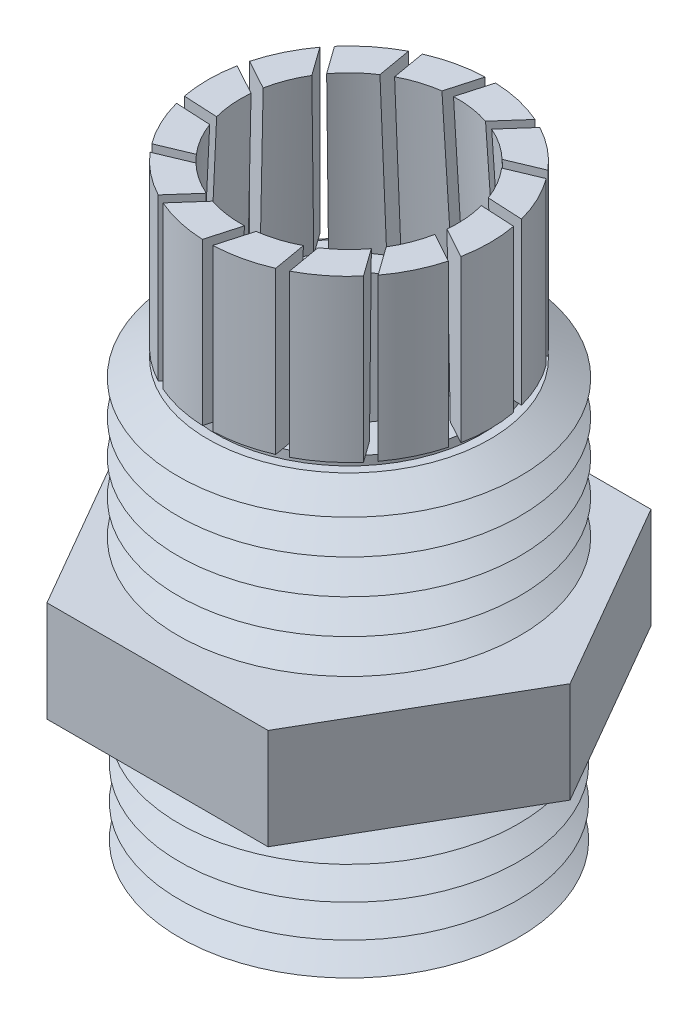
SolidWorks part; units mm, degrees
ref_plane "Front Plane" through (0, 0, 0) normal (0, 0, 1) x (1, 0, 0)
ref_plane "Top Plane" through (0, 0, 0) normal (0, 1, 0) x (1, 0, 0)
ref_plane "Right Plane" through (0, 0, 0) normal (1, 0, 0) x (0, 0, -1)
sketch "Sketch1" plane through (0, 0, 0) normal (0, 0, 1) x (1, 0, 0)
  line L0 (-5, -1.7) -> (-5, -14.9666)
  line L1 (0, -55) -> (0, 55) construction
  line L2 (-7, 7) -> (-7, 15)
  line L4 (-7, -7) -> (-7, -2)
  line L5 (-7, 15) -> (-5.3716, 15)
  line L6 (-5, -1.7) -> (-4.5951, 7)
  line L7 (-7, -14.9666) -> (-8.41, -14.1525)
  line L8 (-7, -2) -> (-8.4815, -1.1446)
  line L9 (-7, -13.3385) -> (-8.41, -14.1525)
  line L10 (-7, -14.9666) -> (-5, -14.9666)
  line L11 (-7, -13.3385) -> (-8.41, -12.5244)
  line L12 (-7, -11.7103) -> (-8.41, -12.5244)
  line L13 (-7, -0.2893) -> (-8.4815, -1.1446)
  line L14 (-7, -11.7103) -> (-8.41, -10.8963)
  line L15 (-7, -10.0822) -> (-8.41, -10.8963)
  line L16 (-7, -10.0822) -> (-8.41, -9.2681)
  line L17 (-7, -8.4541) -> (-8.41, -9.2681)
  line L18 (-7, -0.2893) -> (-8.4815, 0.5661)
  line L19 (-7, -8.4541) -> (-8.41, -7.64)
  line L20 (-7, 1.4215) -> (-8.4815, 0.5661)
  line L21 (-8.41, -7.64) -> (-7, -7)
  line L22 (-7, 6.5537) -> (-6.8008, 6.5537)
  line L23 (-6.8008, 6.5537) -> (-6.5772, 6.5537)
  line L24 (-7, 1.4215) -> (-8.4815, 2.2769)
  line L25 (-7, 3.1322) -> (-8.4815, 2.2769)
  line L26 (-7, 3.1322) -> (-8.4815, 3.9876)
  line L27 (-7, 4.843) -> (-8.4815, 3.9876)
  line L28 (-6.5772, 6.5537) -> (-6.5772, 7)
  line L29 (-7, 4.843) -> (-8.4815, 5.6983)
  line L30 (-7, 6.5537) -> (-8.4815, 5.6983)
  line L32 (-6.5772, 7) -> (-7, 7)
  line L33 (-5.3716, 7) -> (-4.5951, 7)
  line L34 (-5.3716, 15) -> (-5.7537, 7)
  line L35 (-5.7537, 7) -> (-5.3716, 7)
  dimension "D1" = 5
ref_axis "Axis1" through (0, -16.4649, 0) along (0, 1, 0)
revolve "Revolve1" add sketch "Sketch1" angle 360 about axis through (0, -16.4649, 0) along (0, 1, 0)
ref_plane "Plane1" through (0, -4.4666, 0) normal (0, -1, 0) x (1, 0, 0)
sketch "Sketch2" plane through (0, -4.4666, 0) normal (0, -1, 0) x (1, 0, 0)
  line L1 (10.9697, 0) -> (5.4848, 9.5)
  line L2 (5.4848, 9.5) -> (-5.4848, 9.5)
  line L3 (-5.4848, 9.5) -> (-10.9697, 0)
  line L4 (-10.9697, 0) -> (-5.4848, -9.5)
  line L5 (-5.4848, -9.5) -> (5.4848, -9.5)
  line L6 (5.4848, -9.5) -> (10.9697, 0)
  circle A0 centre (0, 0) radius 9.5 construction
extrude "Boss-Extrude1" add sketch "Sketch2" along normal mid plane 5
sketch "Sketch4" plane through (0, 15, 0) normal (0, 1, 0) x (1, 0, 0)
  line L0 (-8.3538, 8.8452) -> (-2.2006, 0.2564)
  line L1 (-2.2006, 0.2564) -> (-2.6279, 0)
  line L2 (-12.0666, 0) -> (12.0666, 0) construction
  line L3 (-2.6279, 0) -> (-8.8013, 8.617)
  line L4 (-8.8013, 8.617) -> (-8.3538, 8.8452)
extrude "Cut-Extrude1" cut sketch "Sketch4" against normal up to surface (8 mm away) up to face at (0, 7, -6.5772)
pattern_circular "CirPattern1" count 14 over 360 about axis through (0, 0, 0) along (0, 1, 0) of "Cut-Extrude1"
sketch "Sketch5" plane through (0, -1.9666, 0) normal (0, 1, 0) x (1, 0, 0)
  circle A0 centre (0, 0) radius 5
  dimension "D1" = 10
extrude "Cut-Extrude2" cut sketch "Sketch5" against normal blind 10
